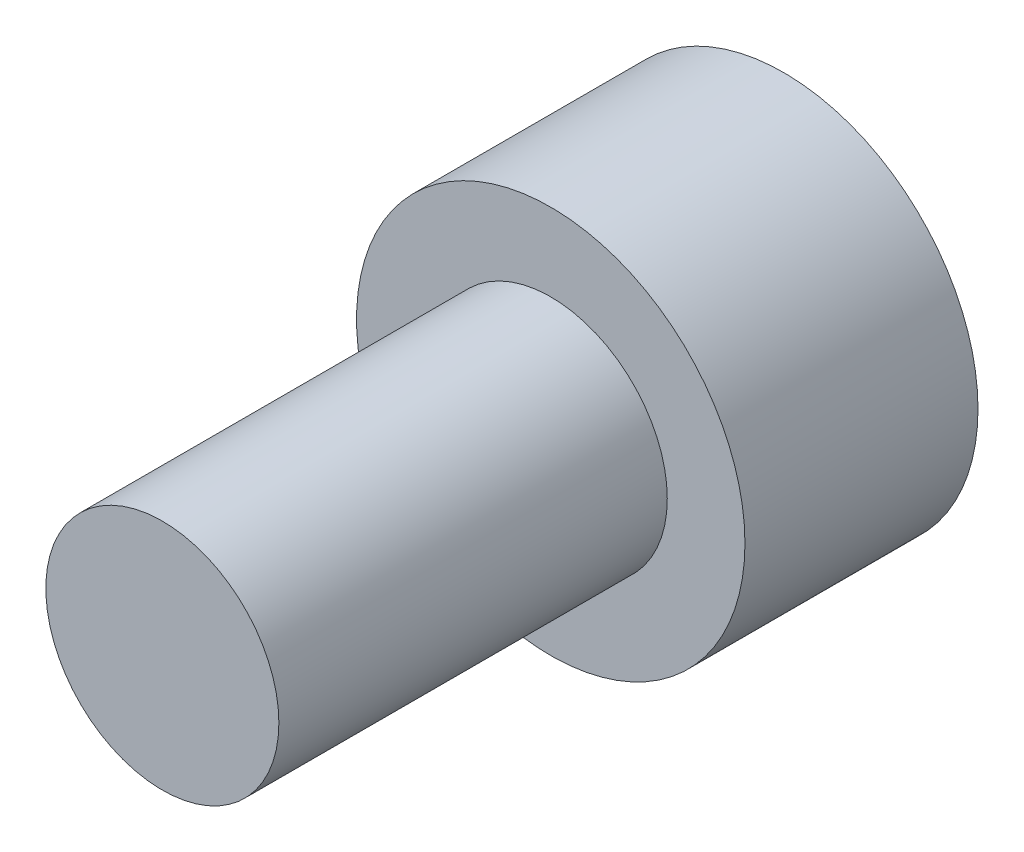
SolidWorks part; units mm, degrees
ref_plane "正面" through (0, 0, 0) normal (0, 0, 1) x (1, 0, 0)
ref_plane "平面" through (0, 0, 0) normal (0, 1, 0) x (1, 0, 0)
ref_plane "右側面" through (0, 0, 0) normal (1, 0, 0) x (0, 0, -1)
sketch "ｽｹｯﾁ1" plane through (0, 0, 0) normal (0, 0, 1) x (1, 0, 0)
  circle A0 centre (0, 0) radius 5
  dimension "D1" = 10
extrude "ﾎﾞｽ - 押し出し1" add sketch "ｽｹｯﾁ1" along normal blind 6
sketch "ｽｹｯﾁ2" plane through (0, 0, 6) normal (0, 0, 1) x (1, 0, 0)
  circle A0 centre (0, 0) radius 3
  dimension "D1" = 6
extrude "ﾎﾞｽ - 押し出し2" add sketch "ｽｹｯﾁ2" along normal blind 10
cosmetic thread "ねじ山1" parameters "D2"=5
sketch "ｽｹｯﾁ3" plane through (0, 0, 0) normal (0, 0, -1) x (-1, 0, 0)
  line L1 (2.4446, 2.3616) -> (-0.8229, 3.2979)
  line L2 (-0.8229, 3.2979) -> (-3.2675, 0.9363)
  line L3 (-3.2675, 0.9363) -> (-2.4446, -2.3616)
  line L4 (-2.4446, -2.3616) -> (0.8229, -3.2979)
  line L5 (0.8229, -3.2979) -> (3.2675, -0.9363)
  line L6 (3.2675, -0.9363) -> (2.4446, 2.3616)
  circle A0 centre (0, 0) radius 2.9436 construction
extrude "ｶｯﾄ - 押し出し1" cut sketch "ｽｹｯﾁ3" against normal blind 3
